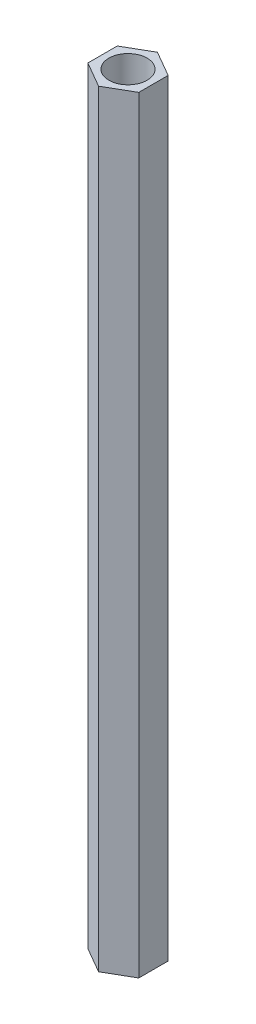
SolidWorks part; units mm, degrees
material "黄铜"
ref_plane "前视基准面" through (0, 0, 0) normal (0, 0, 1) x (1, 0, 0)
ref_plane "上视基准面" through (0, 0, 0) normal (0, 1, 0) x (1, 0, 0)
ref_plane "右视基准面" through (0, 0, 0) normal (1, 0, 0) x (0, 0, -1)
other "Configuration Table"
sketch "草图1" plane through (0, 0, 0) normal (0, 1, 0) x (1, 0, 0)
  line L0 (0, 0) -> (0, 2.2044) construction
  line L1 (0, 2.3) -> (-1.9919, 1.15)
  line L2 (-1.9919, 1.15) -> (-1.9919, -1.15)
  line L3 (-1.9919, -1.15) -> (0, -2.3)
  line L4 (0, -2.3) -> (1.9919, -1.15)
  line L5 (1.9919, -1.15) -> (1.9919, 1.15)
  line L6 (1.9919, 1.15) -> (0, 2.3)
  circle A0 centre (0, 0) radius 1.5
  circle A1 centre (0, 0) radius 1.9919 construction
  dimension "D1" = 3
  dimension "D2" = 4.6
extrude "凸台-拉伸1" add sketch "草图1" along normal blind 60
